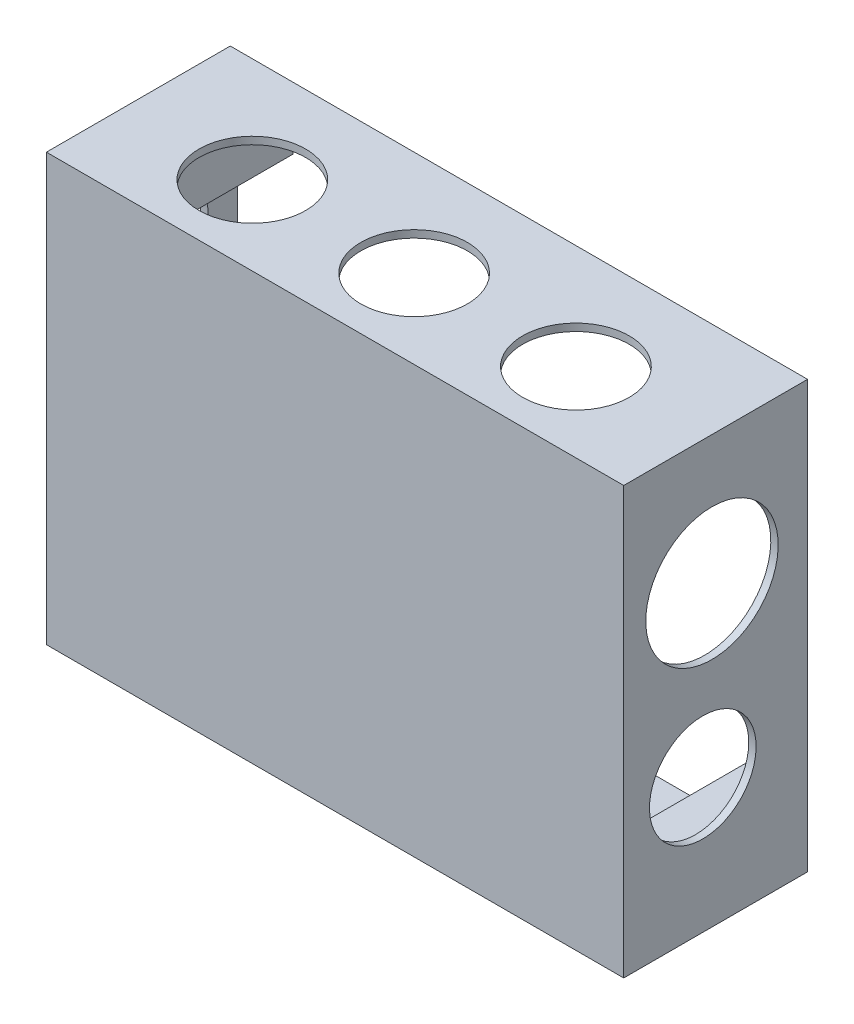
SolidWorks part; units mm, degrees
ref_plane "Plan de face" through (0, 0, 0) normal (0, 0, 1) x (1, 0, 0)
ref_plane "Plan de dessus" through (0, 0, 0) normal (0, 1, 0) x (1, 0, 0)
ref_plane "Plan de droite" through (0, 0, 0) normal (1, 0, 0) x (0, 0, -1)
sketch "Esquisse1" plane through (0, 0, 0) normal (0, 0, 1) x (1, 0, 0)
  line L1 (-78.5, 58) -> (78.5, 58)
  line L2 (-78.5, 58) -> (-78.5, -58)
  line L3 (-78.5, -58) -> (78.5, -58)
  line L4 (78.5, 58) -> (78.5, -58)
  dimension "D1" = 116
  dimension "D2" = 157
  dimension "D3" = 78.5
  dimension "D4" = 58
extrude "Boss.-Extru.1" add sketch "Esquisse1" along normal blind 50
sketch "Esquisse2" plane through (0, 0, 0) normal (0, 0, 1) x (1, 0, 0)
  line L0 (-78.5, 58) -> (-78.5, -58) construction
  line L1 (-61.5, 56) -> (61.5, 56)
  line L2 (-76.5, 41) -> (-76.5, -41)
  line L3 (-61.5, -56) -> (61.5, -56)
  line L4 (76.5, 41) -> (76.5, -41)
  line L5 (78.5, -58) -> (78.5, 58) construction
  line L6 (-78.5, -58) -> (78.5, -58) construction
  line L7 (78.5, 58) -> (-78.5, 58) construction
  line L11 (76.5, 41) -> (61.5, 41)
  line L12 (61.5, 56) -> (61.5, 41)
  line L15 (76.5, -41) -> (61.5, -41)
  line L16 (61.5, -56) -> (61.5, -41)
  line L19 (-76.5, -41) -> (-61.5, -41)
  line L20 (-61.5, -56) -> (-61.5, -41)
  line L23 (-76.5, 41) -> (-61.5, 41)
  line L24 (-61.5, 56) -> (-61.5, 41)
  dimension "D1" = 2
  dimension "D2" = 2
  dimension "D3" = 2
  dimension "D4" = 2
  dimension "D5" = 15
  dimension "D6" = 15
  dimension "D7" = 15
  dimension "D8" = 15
  dimension "D9" = 15
  dimension "D10" = 15
  dimension "D11" = 15
  dimension "D12" = 15
extrude "Enlèv. mat.-Extru.1" cut sketch "Esquisse2" along normal blind 48
sketch "Esquisse3" plane through (78.5, 0, 0) normal (1, 0, 0) x (0, 0, -1)
  line L0 (-50, -58) -> (0, -58) construction
  line L2 (-50, 58) -> (0, 58) construction
  line L3 (-50, -58) -> (-50, 58) construction
  circle A0 centre (-26, 23) radius 18
  circle A1 centre (-28.5, -21.5) radius 14.5
  dimension "D1" = 36
  dimension "D2" = 29
  dimension "D3" = 36.5
  dimension "D4" = 35
  dimension "D5" = 24
  dimension "D6" = 21.5
extrude "Enlèv. mat.-Extru.2" cut sketch "Esquisse3" against normal through all
sketch "Esquisse4" plane through (0, 58, 0) normal (0, 1, 0) x (1, 0, 0)
  line L0 (78.5, -50) -> (78.5, 0) construction
  line L1 (-78.5, -50) -> (-78.5, 0) construction
  line L2 (78.5, -50) -> (-78.5, -50) construction
  circle A0 centre (-44, -28.5) radius 14.5
  circle A1 centre (0, -28.5) radius 14.5
  circle A2 centre (44, -28.5) radius 14.5
  dimension "D1" = 29
  dimension "D2" = 29
  dimension "D3" = 29
  dimension "D4" = 78.5
  dimension "D5" = 34.5
  dimension "D6" = 34.5
  dimension "D7" = 21.5
  dimension "D8" = 21.5
  dimension "D9" = 21.5
extrude "Enlèv. mat.-Extru.3" cut sketch "Esquisse4" against normal through all
sketch "Esquisse5" plane through (0, 0, 48) normal (0, 0, -1) x (-1, 0, 0)
  line L0 (-76.5, -41) -> (-76.5, 41) construction
  line L1 (76.5, 41) -> (76.5, -41) construction
  line L2 (-61.5, 56) -> (61.5, 56) construction
  line L3 (61.5, -56) -> (-61.5, -56) construction
  circle A0 centre (-12.5, -21) radius 3
  circle A1 centre (12.5, -21) radius 3
  circle A2 centre (12.5, 21) radius 3
  circle A3 centre (-12.5, 21) radius 3
  dimension "D8" = 6
  dimension "D9" = 6
  dimension "D10" = 6
  dimension "D11" = 6
  dimension "D1" = 64
  dimension "D2" = 64
  dimension "D3" = 64
  dimension "D4" = 64
  dimension "D5" = 0
  dimension "D6" = 0
  dimension "D7" = 77
  dimension "D12" = 77
extrude "Boss.-Extru.2" add sketch "Esquisse5" along normal blind 5
